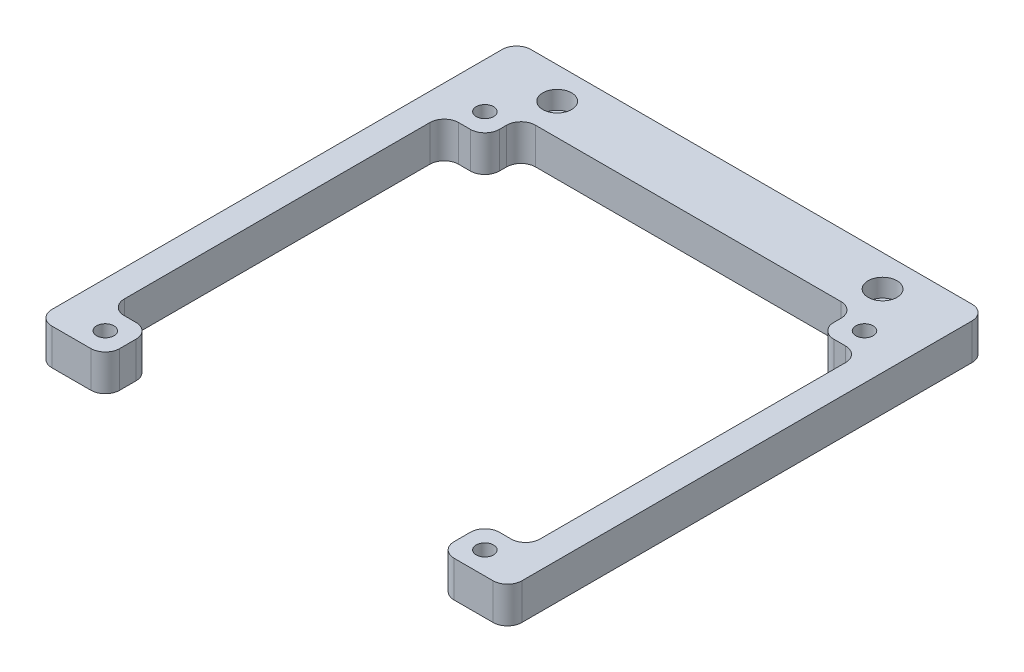
SolidWorks part; units mm, degrees
ref_plane "Front Plane" through (0, 0, 0) normal (0, 0, 1) x (1, 0, 0)
ref_plane "Top Plane" through (0, 0, 0) normal (0, 1, 0) x (1, 0, 0)
ref_plane "Right Plane" through (0, 0, 0) normal (1, 0, 0) x (0, 0, -1)
sketch "Sketch1" plane through (0, 0, 0) normal (0, 1, 0) x (1, 0, 0)
  line L1 (-65, -66.25) -> (65, -66.25)
  line L2 (-65, -66.25) -> (-65, 66.25)
  line L3 (-65, 66.25) -> (65, 66.25)
  line L4 (65, -66.25) -> (65, 66.25)
  line L5 (-65, -66.25) -> (65, 66.25) construction
  line L6 (-65, 66.25) -> (65, -66.25) construction
  point P0 (0, 0)
  dimension "D1" = 132.5
  dimension "D2" = 130
extrude "Boss-Extrude1" add sketch "Sketch1" along normal blind 10
sketch "Sketch2" plane through (0, 10, 0) normal (0, 1, 0) x (1, 0, 0)
  line L0 (-52.5, -60) -> (52.5, -60) construction
  line L1 (0, 66.25) -> (0, -66.25) construction
  line L2 (65, 66.25) -> (-65, 66.25) construction
  line L3 (-65, -66.25) -> (65, -66.25) construction
  line L4 (52.5, -60) -> (52.5, 45) construction
  line L5 (52.5, 45) -> (-52.5, 45) construction
  line L6 (-52.5, 45) -> (-52.5, -60) construction
  line L7 (-52.5, -7.5) -> (0, -7.5) construction
  line L8 (0, -7.5) -> (52.5, -7.5) construction
  circle A0 centre (-52.5, -60) radius 2.4
  circle A1 centre (52.5, -60) radius 2.4
  circle A2 centre (52.5, 45) radius 2.4
  circle A3 centre (-52.5, 45) radius 2.4
  dimension "D1" = 4.8
  dimension "D4" = 6.25
  dimension "D5" = 105
  dimension "D6" = 105
  dimension "D2" = 2
  dimension "D3" = 2
extrude "Cut-Extrude1" cut sketch "Sketch2" against normal through all
sketch "Sketch3" plane through (0, 10, 0) normal (0, 1, 0) x (1, 0, 0)
  line L0 (-65, 66.25) -> (-65, -66.25) construction
  line L1 (-57.5, 38.75) -> (57.5, 38.75)
  line L2 (-57.5, 38.75) -> (-57.5, -53.75)
  line L3 (-57.5, -53.75) -> (57.5, -53.75)
  line L4 (57.5, 38.75) -> (57.5, -53.75)
  line L5 (65, -66.25) -> (65, 66.25) construction
  line L7 (-65, -66.25) -> (65, -66.25) construction
  dimension "D1" = 7.5
  dimension "D2" = 7.5
  dimension "D3" = 92.5
  dimension "D4" = 12.5
extrude "Cut-Extrude2" cut sketch "Sketch3" against normal through all
sketch "Sketch5" plane through (0, 10, 0) normal (0, 1, 0) x (1, 0, 0)
  line L0 (-65, -66.25) -> (65, -66.25) construction
  line L1 (-46.25, -66.25) -> (46.25, -66.25)
  line L2 (-46.25, -66.25) -> (-46.25, 48.75)
  line L3 (-46.25, 48.75) -> (46.25, 48.75)
  line L4 (46.25, -66.25) -> (46.25, 48.75)
  line L5 (-65, 66.25) -> (-65, -66.25) construction
  line L6 (65, -66.25) -> (65, 66.25) construction
  dimension "D1" = 115
  dimension "D2" = 18.75
  dimension "D3" = 18.75
extrude "Cut-Extrude3" cut sketch "Sketch5" against normal through all
fillet "Fillet1" radius 4 16 edges at (-65, 5, 66.25) (65, 5, 66.25) (-65, 5, -66.25) (65, 5, -66.25) (-46.25, 5, 66.25) (-57.5, 5, 53.75) (57.5, 5, 53.75) (46.25, 5, 66.25) (46.25, 5, 53.75) (57.5, 5, -38.75) (46.25, 5, -38.75) (46.25, 5, -48.75) (-46.25, 5, 53.75) (-57.5, 5, -38.75) (-46.25, 5, -48.75) (-46.25, 5, -38.75)
sketch "Sketch6" plane through (0, 10, 0) normal (0, 1, 0) x (1, 0, 0)
  line L0 (-45, 57.5) -> (45, 57.5) construction
  line L1 (0, 66.25) -> (0, 48.75) construction
  line L2 (61, 66.25) -> (-61, 66.25) construction
  line L3 (42.25, 48.75) -> (-42.25, 48.75) construction
  circle A0 centre (-45, 57.5) radius 2.5
  circle A1 centre (45, 57.5) radius 2.5
  point P10 (0, 57.5)
  point P11 (0, 57.5)
  dimension "D1" = 5
  dimension "D2" = 5
  dimension "D3" = 90
extrude "Cut-Extrude4" cut sketch "Sketch6" against normal blind 10
sketch "Sketch7" plane through (0, 10, 0) normal (0, 1, 0) x (1, 0, 0)
  circle A0 centre (-45, 57.5) radius 4
  circle A1 centre (45, 57.5) radius 4
  dimension "D1" = 8
  dimension "D2" = 8
extrude "Cut-Extrude5" cut sketch "Sketch7" against normal blind 5
sketch "Sketch8" plane through (0, 0, 0) normal (0, 1, 0) x (1, 0, 0)
  line L0 (61, 66.25) -> (-61, 66.25) construction
  line L1 (-52.9, 66.25) -> (-57.1, 66.25)
  line L2 (-52.9, 66.25) -> (-52.9, 62.05)
  line L3 (-52.9, 62.05) -> (-57.1, 62.05)
  line L4 (-57.1, 66.25) -> (-57.1, 62.05)
  line L5 (-45, 57.5) -> (-45, 66.25) construction
  line L6 (-37.1, 66.25) -> (-32.9, 66.25)
  line L7 (-37.1, 66.25) -> (-37.1, 62.05)
  line L8 (-37.1, 62.05) -> (-32.9, 62.05)
  line L9 (-32.9, 66.25) -> (-32.9, 62.05)
  line L10 (32.9, 66.25) -> (37.1, 66.25)
  line L11 (32.9, 66.25) -> (32.9, 62.05)
  line L12 (32.9, 62.05) -> (37.1, 62.05)
  line L13 (37.1, 66.25) -> (37.1, 62.05)
  line L14 (52.9, 66.25) -> (57.1, 66.25)
  line L15 (52.9, 66.25) -> (52.9, 62.05)
  line L16 (52.9, 62.05) -> (57.1, 62.05)
  line L17 (57.1, 66.25) -> (57.1, 62.05)
  line L18 (45, 57.5) -> (45, 66.25) construction
  point P20 (-55, 62.05)
  point P21 (-35, 62.05)
  point P26 (35, 62.05)
  point P27 (55, 62.05)
  dimension "D1" = 4.2
  dimension "D2" = 4.2
  dimension "D3" = 10
  dimension "D4" = 10
  dimension "D5" = 10
  dimension "D6" = 10
extrude "Cut-Extrude6" cut sketch "Sketch8" along normal blind 5
sketch "Sketch9" plane through (0, 0, 0) normal (0, -1, 0) x (1, 0, 0)
  circle A0 centre (-52.5, 60) radius 4
  circle A1 centre (52.5, 60) radius 4
  circle A2 centre (-52.5, -45) radius 4
  circle A3 centre (52.5, -45) radius 4
  dimension "D1" = 8
extrude "Cut-Extrude7" cut sketch "Sketch9" against normal blind 5
